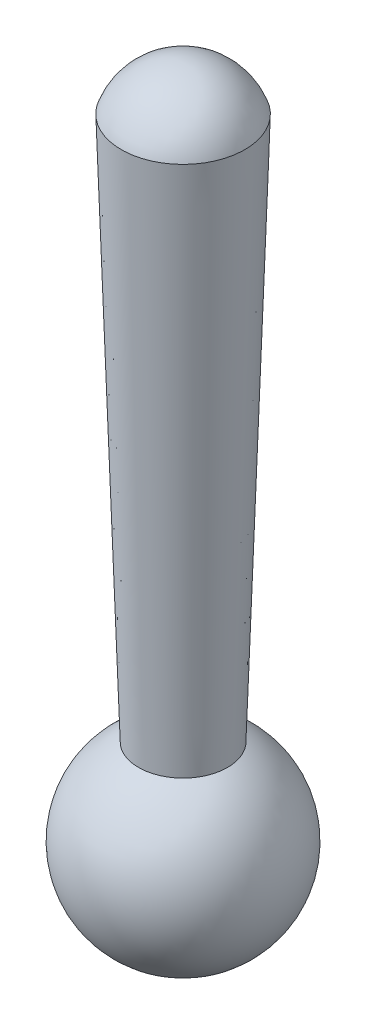
SolidWorks part; units mm, degrees
ref_plane "Front Plane" through (0, 0, 0) normal (0, 0, 1) x (1, 0, 0)
ref_plane "Top Plane" through (0, 0, 0) normal (0, 1, 0) x (1, 0, 0)
ref_plane "Right Plane" through (0, 0, 0) normal (1, 0, 0) x (0, 0, -1)
sketch "Sketch1" plane through (0, 0, 0) normal (0, 0, 1) x (1, 0, 0)
  line L0 (-0.9, 1.7411) -> (-1.25, 12.7411)
  line L1 (0, 1.96) -> (0, 16.1224) construction
  line L2 (0.9, 1.7411) -> (1.25, 12.7411)
  line L3 (0, 13.6396) -> (0, -1.96)
  arc A0 (-0.9, 1.7411) -> (0.9, 1.7411) centre (0, 0) ccw
  arc A1 (-1.25, 12.7411) -> (1.25, 12.7411) centre (0, 12.3208) cw
  dimension "D1" = 3.92
  dimension "D2" = 1.8
  dimension "D3" = 2.5
  dimension "D4" = 11
revolve "Revolve1" add sketch "Sketch1" angle 360 about L1
